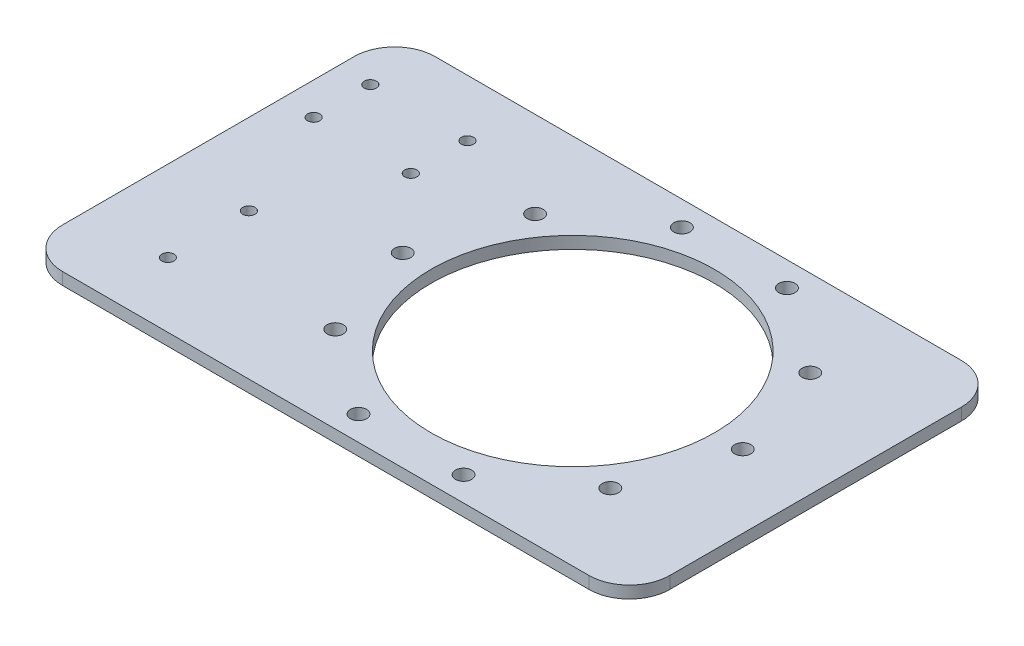
SolidWorks part; units mm, degrees
ref_plane "前基準面" through (0, 0, 0) normal (0, 0, 1) x (1, 0, 0)
ref_plane "上基準面" through (0, 0, 0) normal (0, 1, 0) x (1, 0, 0)
ref_plane "右基準面" through (0, 0, 0) normal (1, 0, 0) x (0, 0, -1)
sketch "草圖1" plane through (0, 0, 0) normal (0, 1, 0) x (1, 0, 0)
  line L1 (-75, 46) -> (75, 46)
  line L2 (-75, 46) -> (-75, -46)
  line L3 (-75, -46) -> (75, -46)
  line L4 (75, 46) -> (75, -46)
  line L5 (-75, 46) -> (75, -46) construction
  line L6 (-75, -46) -> (75, 46) construction
  circle A0 centre (15, 0) radius 35
  point P0 (0, 0)
  dimension "D3" = 70
  dimension "D1" = 92
  dimension "D2" = 150
  dimension "D4" = 15
extrude "填料-伸長1" add sketch "草圖1" along normal blind 3
sketch "草圖2" plane through (0, 3, 0) normal (0, 1, 0) x (1, 0, 0)
  circle A0 centre (15, 0) radius 42 construction
  circle A1 centre (15, 0) radius 35 construction
  circle A2 centre (57, 0) radius 2
  dimension "D1" = 84
  dimension "D2" = 4
extrude "除料-伸長1" cut sketch "草圖2" against normal up to next
pattern_circular "環狀複製排列1" count 10 over 360 about axis through (15, 0, 0) along (0, 1, 0) of "除料-伸長1"
sketch "草圖3" plane through (0, 3, 0) normal (0, 1, 0) x (1, 0, 0)
  line L0 (-75, 46) -> (-75, -46) construction
  line L1 (-75, 40) -> (-35, 40) construction
  line L2 (-75, 40) -> (-75, -40) construction
  line L3 (-75, -40) -> (-35, -40) construction
  line L4 (-35, 40) -> (-35, -40) construction
  line L5 (-75, 40) -> (-35, -40) construction
  line L6 (-75, -40) -> (-35, 40) construction
  line L7 (-75, 10) -> (-35, 10) construction
  line L8 (-55, 40) -> (-55, 10) construction
  circle A0 centre (-67, 32) radius 1.5
  circle A1 centre (-67, 18) radius 1.5
  circle A2 centre (-43, 18) radius 1.5
  circle A3 centre (-43, 32) radius 1.5
  circle A4 centre (-55, -10) radius 1.5
  circle A5 centre (-55, -30) radius 1.5
  point P0 (-55, 0)
  dimension "D7" = 3
  dimension "D1" = 40
  dimension "D2" = 80
  dimension "D3" = 30
  dimension "D4" = 8
  dimension "D5" = 8
  dimension "D6" = 8
  dimension "D8" = 20
  dimension "D9" = 20
extrude "除料-伸長2" cut sketch "草圖3" against normal blind 3
fillet "圓角1" radius 10 4 edges at (-75, 1.5, -46) (-75, 1.5, 46) (75, 1.5, 46) (75, 1.5, -46)
